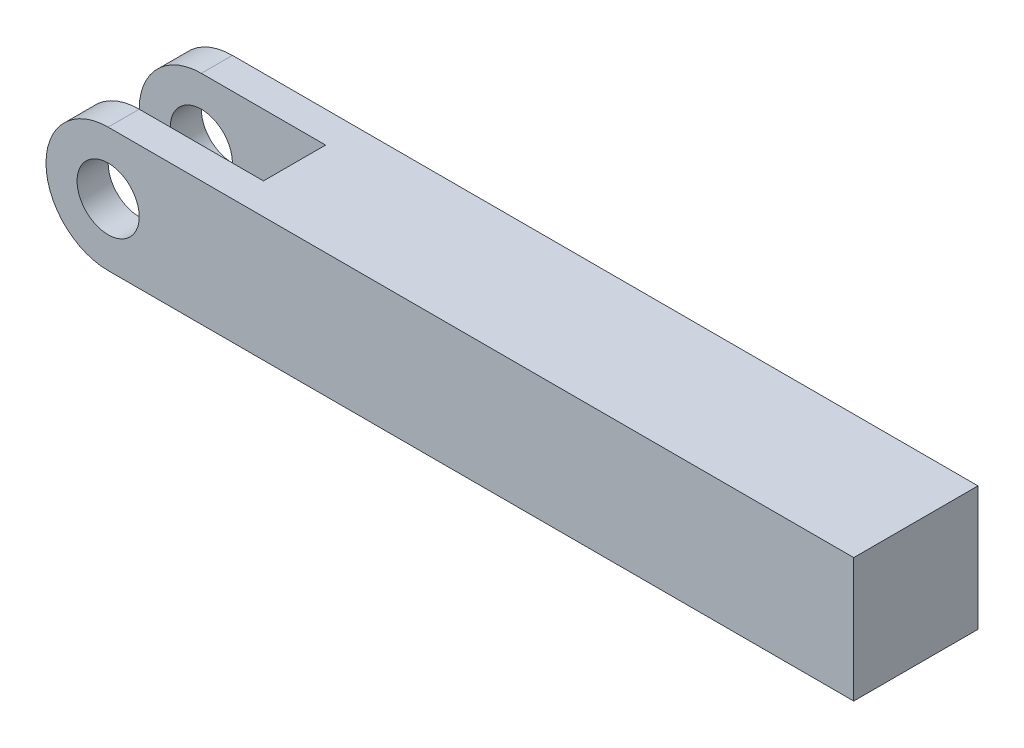
SolidWorks part; units mm, degrees
ref_plane "前视基准面" through (0, 0, 0) normal (0, 0, 1) x (1, 0, 0)
ref_plane "上视基准面" through (0, 0, 0) normal (0, 1, 0) x (1, 0, 0)
ref_plane "右视基准面" through (0, 0, 0) normal (1, 0, 0) x (0, 0, -1)
other "Configuration Table"
sketch "草图1" plane through (0, 0, 0) normal (0, 0, 1) x (1, 0, 0)
  line L1 (-25, -5) -> (25, -5)
  line L2 (-25, -5) -> (-25, 5)
  line L3 (-25, 5) -> (25, 5)
  line L4 (25, -5) -> (25, 5)
  line L5 (-25, -5) -> (25, 5) construction
  line L6 (-25, 5) -> (25, -5) construction
  point P0 (0, 0)
  dimension "D1" = 10
  dimension "D2" = 50
extrude "凸台-拉伸1" add sketch "草图1" along normal mid plane 10
sketch "草图2" plane through (0, 0, -5) normal (0, 0, -1) x (-1, 0, 0)
  line L0 (25, 5) -> (25, -5) construction
  line L1 (25, 5) -> (35, 5)
  line L2 (35, -5) -> (25, -5)
  line L3 (25, -5) -> (25, 5)
  circle A1 centre (35, 0) radius 2.5
  arc A2 (35, -5) -> (35, 5) centre (35, 0) ccw
  dimension "D2" = 5
  dimension "D4" = 10
  dimension "D3" = 10
extrude "凸台-拉伸2" add sketch "草图2" against normal blind 2.5
mirror "镜向1" about plane through (0, 0, 0) normal (0, 0, 1) of "凸台-拉伸2"
sketch "草图3" plane through (0, 0, -5) normal (0, 0, -1) x (-1, 0, 0)
  circle A0 centre (35, 0) radius 2.5
sketch "草图4" plane through (0, 0, 5) normal (0, 0, 1) x (1, 0, 0)
  circle A0 centre (-35, 0) radius 9.208
